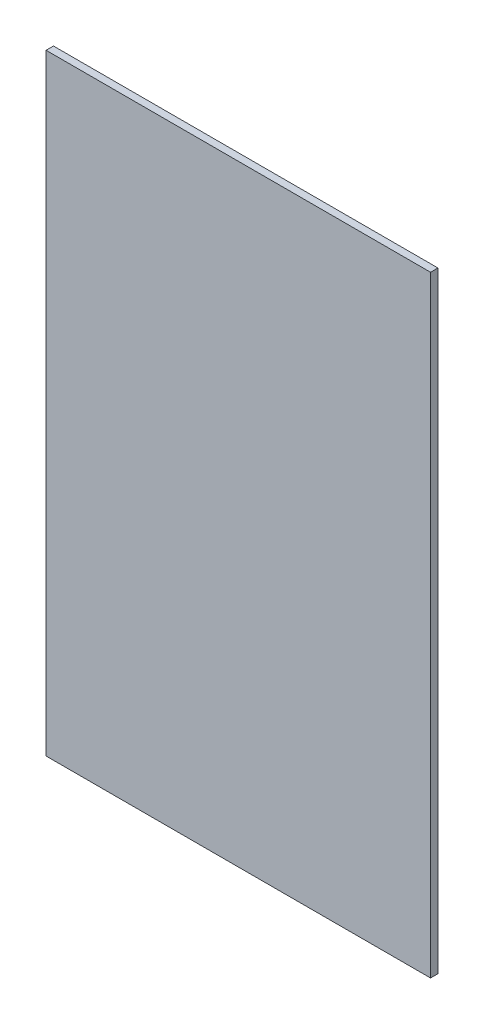
SolidWorks part; units mm, degrees
ref_plane "Plan de face" through (0, 0, 0) normal (0, 0, 1) x (1, 0, 0)
ref_plane "Plan de dessus" through (0, 0, 0) normal (0, 1, 0) x (1, 0, 0)
ref_plane "Plan de droite" through (0, 0, 0) normal (1, 0, 0) x (0, 0, -1)
sketch "Esquisse1" plane through (0, 0, 0) normal (0, 0, 1) x (1, 0, 0)
  line L1 (0.917, 196.4934) -> (156.917, 196.4934)
  line L2 (0.917, 196.4934) -> (0.917, -51.5066)
  line L3 (0.917, -51.5066) -> (156.917, -51.5066)
  line L4 (156.917, 196.4934) -> (156.917, -51.5066)
  dimension "D1" = 248
  dimension "D2" = 156
extrude "Boss.-Extru.1" add sketch "Esquisse1" along normal blind 3
